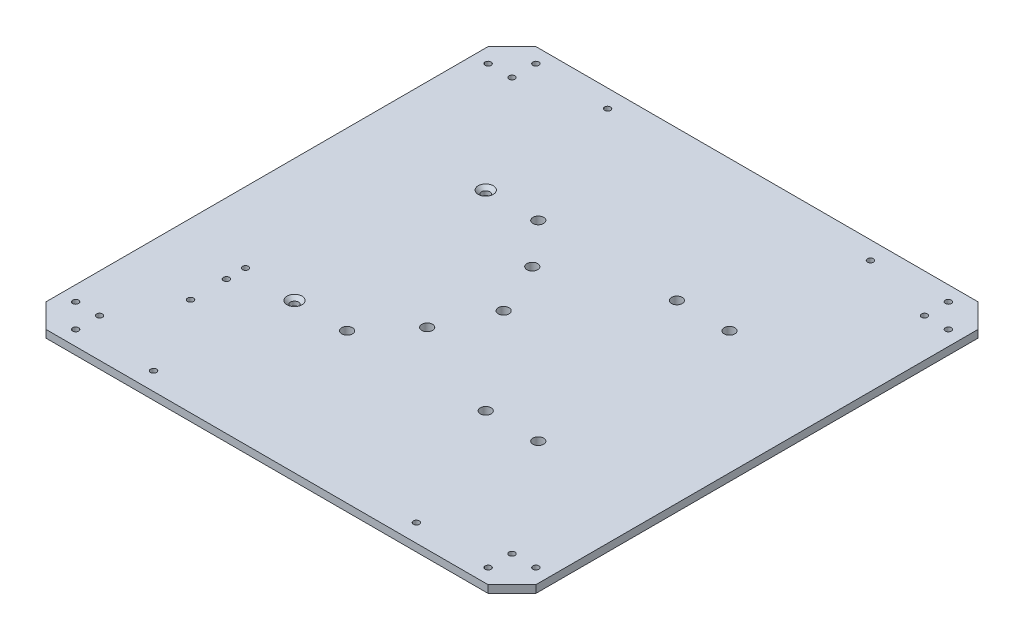
SolidWorks part; units mm, degrees
material "6061-T6 (SS)"
ref_plane "Front Plane" through (0, 0, 0) normal (0, 0, 1) x (1, 0, 0)
ref_plane "Top Plane" through (0, 0, 0) normal (0, 1, 0) x (1, 0, 0)
ref_plane "Right Plane" through (0, 0, 0) normal (1, 0, 0) x (0, 0, -1)
sketch "Sketch1" plane through (0, 0, 0) normal (0, 1, 0) x (1, 0, 0)
  line L0 (-102.5, 102.5) -> (102.5, -102.5) construction
  line L1 (-92.5, 102.5) -> (92.5, 102.5)
  line L2 (-102.5, 92.5) -> (-102.5, -92.5)
  line L3 (-92.5, -102.5) -> (92.5, -102.5)
  line L4 (102.5, 92.5) -> (102.5, -92.5)
  line L5 (92.5, -102.5) -> (102.5, -92.5)
  line L6 (92.5, 102.5) -> (102.5, 92.5)
  line L7 (-102.5, 92.5) -> (-92.5, 102.5)
  line L8 (-102.5, -92.5) -> (-92.5, -102.5)
  point P2 (-102.5, -102.5)
  point P3 (102.5, 102.5)
  dimension "D1" = 205
  dimension "D2" = 205
extrude "Boss-Extrude1" add sketch "Sketch1" along normal blind 3.175
sketch "Sketch2" plane through (0, 3.175, 0) normal (0, 1, 0) x (1, 0, 0)
  circle A0 centre (-51, -40) radius 1.5
  circle A2 centre (-29, -40) radius 2.25
  circle A5 centre (-51, 40) radius 1.5
  circle A6 centre (-29, 40) radius 2.25
  circle A9 centre (29, 40) radius 2.25
  circle A10 centre (51, 40) radius 2.25
  circle A14 centre (29, -40) radius 2.25
  circle A15 centre (51, -40) radius 2.25
  circle A16 centre (-3.5, 0) radius 2.25
  circle A17 centre (-13.5, 22) radius 2.25
  circle A18 centre (-13.5, -22) radius 2.25
  dimension "D1" = 3
  dimension "D2" = 4.5
extrude "Cut-Extrude1" cut sketch "Sketch2" against normal through all
hole_wizard "M3x0.5 Tapped Hole1" positions "Sketch4" profile "Sketch3" tap size "M3x0.5" standard "Ansi Metric" end condition through all
sketch "Sketch4" plane through (0, 3.175, 0) normal (0, 1, 0) x (-1, 0, 0)
  line L0 (92.5, 102.5) -> (-92.5, 102.5) construction
  line L1 (102.5, -92.5) -> (102.5, 92.5) construction
  line L2 (-92.5, -102.5) -> (92.5, -102.5) construction
  line L3 (-102.5, 92.5) -> (-102.5, -92.5) construction
  point P0 (96.3, -86.3)
  point P1 (86.3, -96.3)
  point P3 (-86.3, -96.3)
  point P5 (-96.3, -86.3)
  point P7 (-96.3, 86.3)
  point P9 (-86.3, 96.3)
  point P11 (86.3, 96.3)
  point P13 (96.3, 86.3)
  point P32 (-86.3, 86.3)
  point P34 (-86.3, -86.3)
  point P36 (86.3, -86.3)
  point P38 (86.3, 86.3)
  dimension "D1" = 16.2
  dimension "D2" = 6.2
  dimension "D3" = 6.2
  dimension "D4" = 16.2
  dimension "D5" = 16.2
  dimension "D6" = 6.2
  dimension "D7" = 6.2
  dimension "D8" = 16.2
sketch "Sketch3" plane through (-96.3, 3.175, -86.3) normal (1, 0, 0) x (0, 0, 1)
  line L0 (0, 0) -> (0, 3.175)
  line L1 (0, 3.175) -> (1.25, 3.175)
  line L2 (1.25, 3.175) -> (1.25, 0)
  line L5 (1.25, 0) -> (0, 0)
  line L11 (0, -6.35) -> (0, 107.95) construction
  dimension "Thru Tap Drill Dia." = 2.5
  dimension "Thru Tap Drill Depth" = 3.175
cosmetic thread "Hole Thread1" parameters "D2"=3
cosmetic thread "Hole Thread2" parameters "D2"=3
cosmetic thread "Hole Thread3" parameters "D2"=3
cosmetic thread "Hole Thread4" parameters "D2"=3
cosmetic thread "Hole Thread5" parameters "D2"=3
cosmetic thread "Hole Thread6" parameters "D2"=3
cosmetic thread "Hole Thread7" parameters "D2"=3
cosmetic thread "Hole Thread8" parameters "D2"=3
cosmetic thread "Hole Thread9" parameters "D2"=3
cosmetic thread "Hole Thread10" parameters "D2"=3
cosmetic thread "Hole Thread11" parameters "D2"=3
cosmetic thread "Hole Thread12" parameters "D2"=3
sketch "Sketch5" plane through (0, 3.175, 0) normal (0, 1, 0) x (1, 0, 0)
  circle A0 centre (-55, 95) radius 1.25
  circle A1 centre (55, 95) radius 1.25
  circle A2 centre (-55, -95) radius 1.25
  circle A3 centre (55, -95) radius 1.25
  dimension "D1" = 2.5
extrude "Cut-Extrude2" cut sketch "Sketch5" against normal through all
sketch "Sketch6" plane through (0, 3.175, 0) normal (0, 1, 0) x (1, 0, 0)
  line L0 (-92.5, -102.5) -> (92.5, -102.5) construction
  line L1 (-102.5, 92.5) -> (-102.5, -92.5) construction
  circle A0 centre (-73, -46.5) radius 1.25
  circle A1 centre (-73, -38.5) radius 1.25
  circle A2 centre (-73, -61.5) radius 1.25
  dimension "D3" = 2.5
  dimension "D1" = 56
  dimension "D2" = 29.5
  dimension "D4" = 8
  dimension "D5" = 15
extrude "Cut-Extrude3" cut sketch "Sketch6" against normal blind 10
hole_wizard "CSK for M3 Flat Head Machine Screw1" positions "Sketch8" profile "Sketch7" countersink size "M3" standard "Ansi Metric" end condition through all
sketch "Sketch8" plane through (0, 3.175, 0) normal (0, 1, 0) x (-1, 0, 0)
  point P0 (51, -40)
  point P1 (51, 40)
sketch "Sketch7" plane through (-51, 3.175, -40) normal (1, 0, 0) x (0, 0, 1)
  line L0 (0, 0) -> (0, 3.175)
  line L1 (0, 3.175) -> (1.7, 3.175)
  line L2 (1.7, 3.175) -> (1.7, 1.45)
  line L3 (1.7, 1.45) -> (3.15, 0)
  line L5 (3.15, 0) -> (0, 0)
  line L6 (-1.7, 1.45) -> (-3.15, 0) construction
  line L11 (0, -6.35) -> (0, 107.95) construction
  dimension "Thru Hole Dia." = 3.4
  dimension "Thru Hole Depth" = 3.175
  dimension "Near C'Sink Dia." = 6.3
  dimension "Near C'Sink Angle" = 90
other "Move Face1" face at (0, 1.5875, -102.5) parameters "D1"=16
